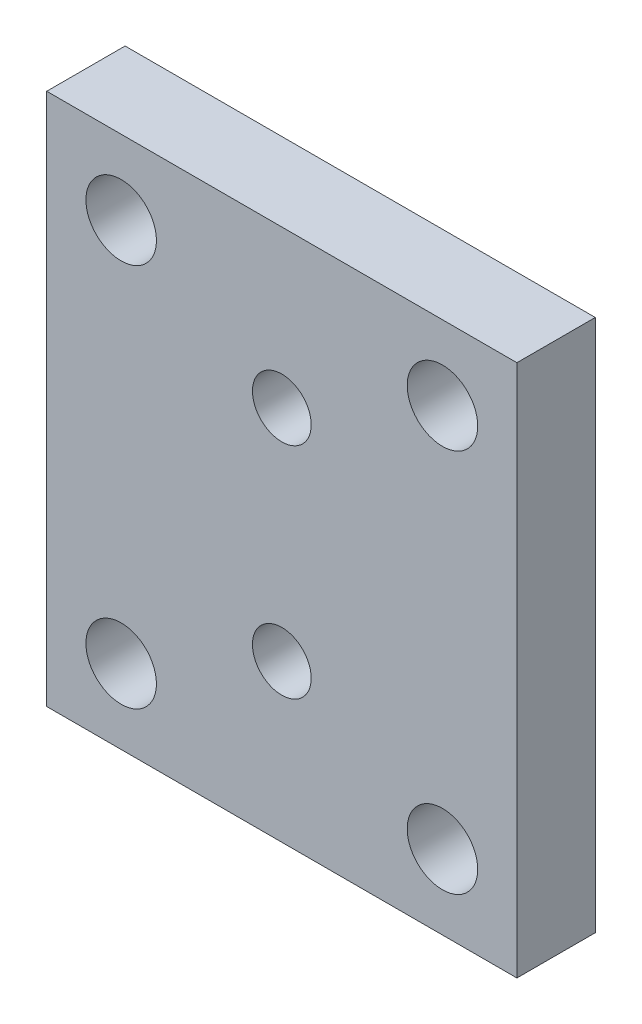
SolidWorks part; units mm, degrees
ref_plane "Front Plane" through (0, 0, 0) normal (0, 0, 1) x (1, 0, 0)
ref_plane "Top Plane" through (0, 0, 0) normal (0, 1, 0) x (1, 0, 0)
ref_plane "Right Plane" through (0, 0, 0) normal (1, 0, 0) x (0, 0, -1)
sketch "Sketch1" plane through (0, 0, 0) normal (0, 0, 1) x (1, 0, 0)
  line L1 (0, 0) -> (30, 0)
  line L2 (0, 0) -> (0, 34)
  line L3 (0, 34) -> (30, 34)
  line L4 (30, 0) -> (30, 34)
  circle A0 centre (4.75, 29.25) radius 2.25
  circle A1 centre (25.25, 29.25) radius 2.25
  circle A2 centre (25.25, 4.75) radius 2.25
  circle A3 centre (4.75, 4.75) radius 2.25
  circle A4 centre (15, 24) radius 1.875
  circle A5 centre (15, 10) radius 1.875
  dimension "D3" = 4.5
  dimension "D6" = 4.5
  dimension "D13" = 4.5
  dimension "D14" = 4.5
  dimension "D15" = 3.75
  dimension "D16" = 3.75
  dimension "D1" = 34
  dimension "D2" = 30
  dimension "D4" = 4.75
  dimension "D5" = 4.75
  dimension "D7" = 4.75
  dimension "D8" = 4.75
  dimension "D9" = 4.75
  dimension "D10" = 4.75
  dimension "D11" = 4.75
  dimension "D12" = 4.75
  dimension "D17" = 15
  dimension "D18" = 15
  dimension "D19" = 10
  dimension "D20" = 10
extrude "Boss-Extrude1" add sketch "Sketch1" along normal blind 5
